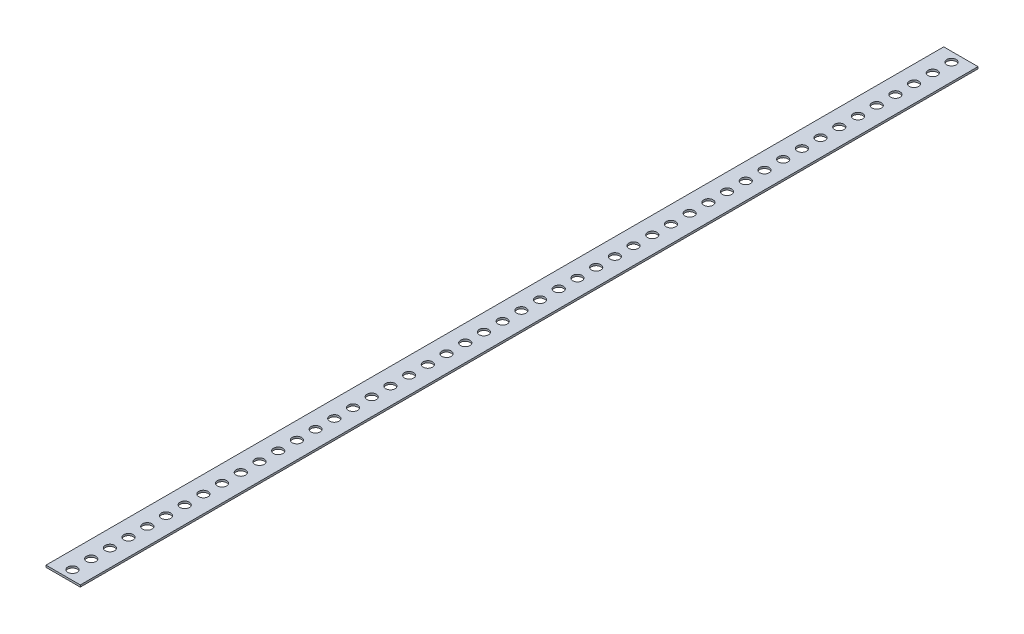
SolidWorks part; units mm, degrees
material "Galvanized Steel"
ref_plane "Front Plane" through (0, 0, 0) normal (0, 0, 1) x (1, 0, 0)
ref_plane "Top Plane" through (0, 0, 0) normal (0, 1, 0) x (1, 0, 0)
ref_plane "Right Plane" through (0, 0, 0) normal (1, 0, 0) x (0, 0, -1)
sketch "Sketch1" plane through (0, 0, 0) normal (0, 1, 0) x (1, 0, 0)
  line L1 (-17.4625, 457.2) -> (17.4625, 457.2) construction
  line L2 (-17.4625, 457.2) -> (-17.4625, -457.2) construction
  line L3 (-17.4625, -457.2) -> (17.4625, -457.2) construction
  line L4 (17.4625, 457.2) -> (17.4625, -457.2) construction
  line L5 (-17.4625, 457.2) -> (17.4625, -457.2) construction
  line L6 (-17.4625, -457.2) -> (17.4625, 457.2) construction
  line L8 (0, -457.2) -> (0, -447.675) construction
  circle A0 centre (0, -447.675) radius 4.7625 construction
  circle A2 centre (0, -428.625) radius 4.7625 construction
  point P0 (0, 0)
  point P13 (0, -387.35)
  point P19 (0, 387.35)
  dimension "D1" = 9.525
  dimension "Length" = 914.4
  dimension "Width (A)" = 34.925
  dimension "D3" = 19.05
  dimension "D4" = 9.525
  dimension "D5" = 69.85
  dimension "D6" = 69.85
sketch "Sketch2" plane through (0, 0, 0) normal (1, 0, 0) x (0, 0, -1)
  line L0 (0, -0.9919) -> (0, 0.9919) construction
  dimension "Thickness" = 1.9837
sketch "Sketch3" plane through (0, 0, 0) normal (0, 1, 0) x (1, 0, 0)
  line L0 (-17.4625, 457.2) -> (17.4625, 457.2) construction
  line L1 (17.4625, 457.2) -> (17.4625, -457.2) construction
  line L2 (-17.4625, -457.2) -> (17.4625, -457.2) construction
  line L3 (-17.4625, 457.2) -> (-17.4625, -457.2) construction
  line L4 (-17.4625, 457.2) -> (17.4625, 457.2)
  line L5 (17.4625, 457.2) -> (17.4625, -457.2)
  line L6 (-17.4625, -457.2) -> (17.4625, -457.2)
  line L7 (-17.4625, 457.2) -> (-17.4625, -457.2)
extrude "Boss-Extrude1" add sketch "Sketch3" against normal up to vertex (0.9919 mm away) and the other way up to vertex (0.9919 mm away) up to point (0, -0.9919, 0) other way up to point (0, 0.9919, 0)
sketch "Sketch4" plane through (0, 0.9919, 0) normal (0, 1, 0) x (1, 0, 0)
  circle A0 centre (0, -447.675) radius 4.7625 construction
  circle A1 centre (0, -447.675) radius 4.7625
extrude "Cut-Extrude1" cut sketch "Sketch4" against normal up to next
pattern_linear "LPattern1" count 53 spacing 19.05 along (0, 0, -1) of "Cut-Extrude1"
equation "\"D4@Sketch1\"=\"D3@Sketch1\"/2"
equation "\"D3@Sketch1\"=\"D1@Sketch1\"*2"
equation "\"D3@LPattern1\"=\"D3@Sketch1\""
equation "\"D1@LPattern1\"=( \"Length@Sketch1\" / \"D3@Sketch1\" ) + 5"
equation "\"D5@Sketch1\"=\"Width (A)@Sketch1\"*2"
equation "\"D6@Sketch1\"=\"D5@Sketch1\""
